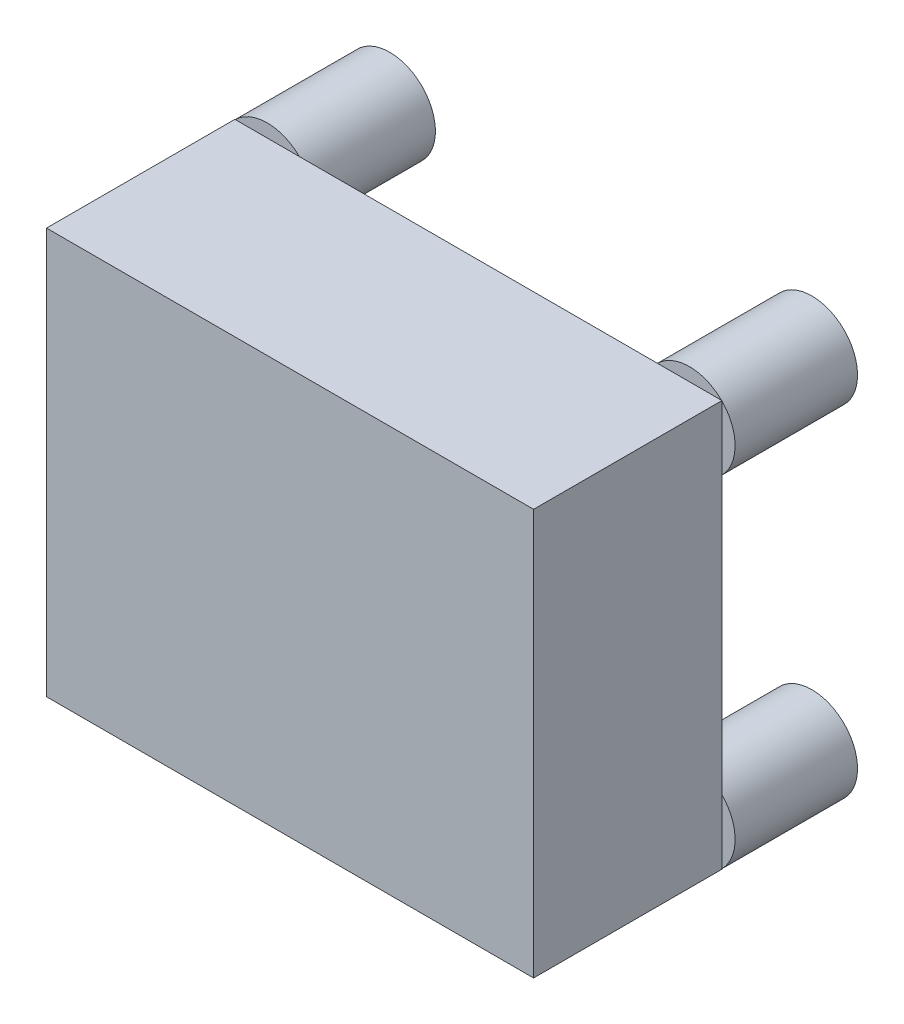
SolidWorks part; units mm, degrees
ref_plane "Front Plane" through (0, 0, 0) normal (0, 0, 1) x (1, 0, 0)
ref_plane "Top Plane" through (0, 0, 0) normal (0, 1, 0) x (1, 0, 0)
ref_plane "Right Plane" through (0, 0, 0) normal (1, 0, 0) x (0, 0, -1)
sketch "Sketch1" plane through (0, 0, 0) normal (0, 0, 1) x (1, 0, 0)
  line L1 (0, 0) -> (38.1, 0)
  line L2 (0, 0) -> (0, 31.75)
  line L3 (0, 31.75) -> (38.1, 31.75)
  line L4 (38.1, 0) -> (38.1, 31.75)
  dimension "D1" = 31.75
  dimension "D2" = 38.1
extrude "Boss-Extrude1" add sketch "Sketch1" along normal blind 14.732
sketch "Sketch2" plane through (0, 0, 0) normal (0, 0, -1) x (-1, 0, 0)
  line L0 (-38.1, 2.54) -> (-35.56, 2.54) construction
  line L1 (-38.1, 0) -> (-38.1, 31.75) construction
  line L2 (-35.56, 2.54) -> (-35.56, 0) construction
  line L3 (0, 0) -> (-38.1, 0) construction
  line L4 (-2.54, 2.54) -> (0, 2.54) construction
  line L5 (0, 31.75) -> (0, 0) construction
  line L6 (-35.56, 29.21) -> (-35.56, 31.75) construction
  line L7 (-38.1, 31.75) -> (0, 31.75) construction
  circle A0 centre (-35.56, 2.54) radius 3.5687
  circle A1 centre (-2.54, 2.54) radius 3.5687
  circle A2 centre (-35.56, 29.21) radius 3.5687
  circle A3 centre (-2.54, 29.21) radius 3.5687
  dimension "D3" = 7.1374
  dimension "D5" = 7.1374
  dimension "D7" = 7.1374
  dimension "D8" = 7.1374
  dimension "D1" = 2.54
  dimension "D2" = 2.54
  dimension "D4" = 2.54
  dimension "D6" = 2.54
extrude "Boss-Extrude2" add sketch "Sketch2" along normal blind 9.5758
sketch "Sketch3" plane through (0, 0, -9.5758) normal (0, 0, -1) x (-1, 0, 0)
  circle A0 centre (-35.56, 29.21) radius 1.3462
  circle A1 centre (-2.54, 29.21) radius 1.3462
  circle A2 centre (-2.54, 2.54) radius 1.3462
  circle A3 centre (-35.56, 2.54) radius 1.3462
  dimension "D1" = 2.6924
  dimension "D2" = 2.6924
  dimension "D3" = 2.6924
  dimension "D4" = 2.6924
extrude "Cut-Extrude1" cut sketch "Sketch3" against normal blind 8.89
